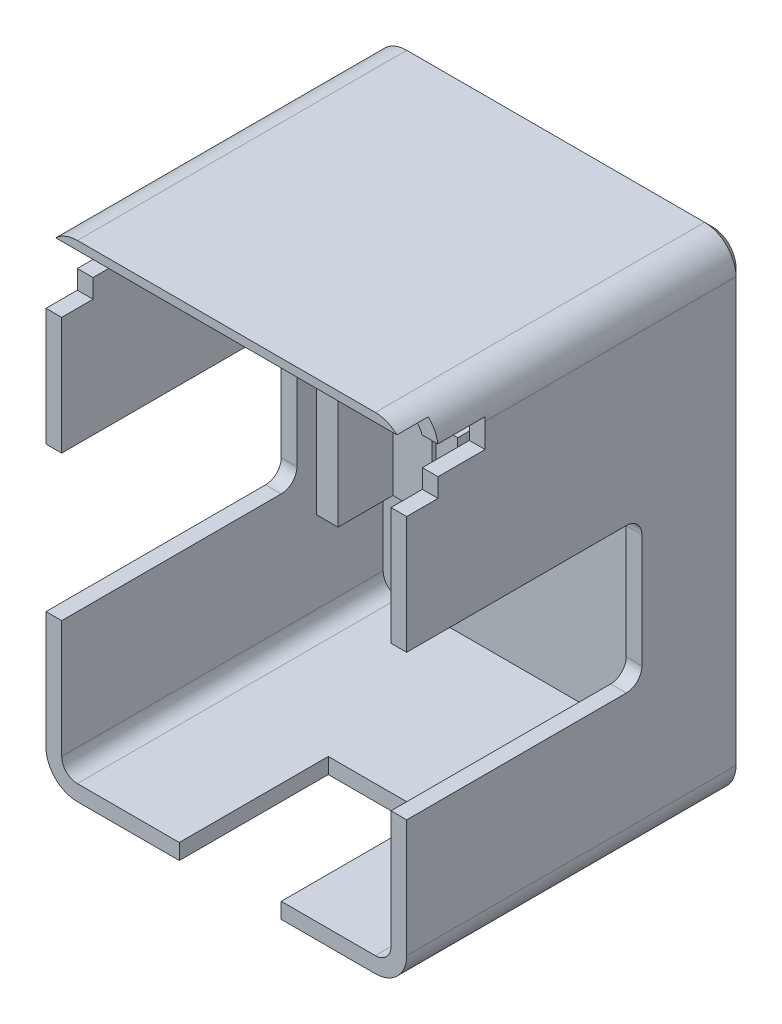
SolidWorks part; units mm, degrees
ref_plane "Plan de face" through (0, 0, 0) normal (0, 0, 1) x (1, 0, 0)
ref_plane "Plan de dessus" through (0, 0, 0) normal (0, 1, 0) x (1, 0, 0)
ref_plane "Plan de droite" through (0, 0, 0) normal (1, 0, 0) x (0, 0, -1)
sketch "Esquisse1" plane through (0, 0, 0) normal (0, 0, 1) x (1, 0, 0)
  line L1 (4, 0) -> (42, 0)
  line L2 (0, 4) -> (0, 58)
  line L3 (4, 62) -> (42, 62)
  line L4 (46, 4) -> (46, 58)
  arc A0 (42, 0) -> (46, 4) centre (42, 4) ccw
  arc A1 (0, 4) -> (4, 0) centre (4, 4) ccw
  arc A2 (0, 58) -> (4, 62) centre (4, 58) cw
  arc A3 (46, 58) -> (42, 62) centre (42, 58) ccw
  point P7 (46, 0)
  point P10 (0, 0)
  point P15 (46, 62)
  dimension "D3" = 4
  dimension "D1" = 46
  dimension "D2" = 62
extrude "Boss.-Extru.1" add sketch "Esquisse1" along normal blind 43
sketch "Esquisse3" plane through (0, 0, 43) normal (0, 0, 1) x (1, 0, 0)
  line L8 (2, 58) -> (2, 4)
  line L9 (4, 2) -> (42, 2)
  line L10 (44, 4) -> (44, 58)
  line L11 (42, 60) -> (4, 60)
  line L12 (2, 58) -> (2, 4)
  line L13 (4, 2) -> (42, 2)
  line L14 (44, 4) -> (44, 58)
  line L15 (42, 60) -> (4, 60)
  arc A4 (42, 2) -> (44, 4) centre (42, 4) ccw
  arc A5 (42, 2) -> (44, 4) centre (42, 4) ccw
  arc A6 (44, 58) -> (42, 60) centre (42, 58) ccw
  arc A7 (44, 58) -> (42, 60) centre (42, 58) ccw
  arc A8 (4, 60) -> (2, 58) centre (4, 58) ccw
  arc A9 (4, 60) -> (2, 58) centre (4, 58) ccw
  arc A10 (2, 4) -> (4, 2) centre (4, 4) ccw
  arc A11 (2, 4) -> (4, 2) centre (4, 4) ccw
  dimension "D1" = 2
extrude "Enlèv. mat.-Extru.1" cut sketch "Esquisse3" against normal blind 41
sketch "Esquisse4" plane through (46, 0, 0) normal (1, 0, 0) x (0, 0, -1)
  line L0 (-43, 62) -> (0, 62) construction
  line L1 (-58.5085, 60.9) -> (-39, 60.9)
  line L2 (-58.5085, 60.9) -> (-58.5085, 52.5)
  line L3 (-58.5085, 52.5) -> (-39, 52.5)
  line L4 (-39, 60.9) -> (-39, 58.5)
  line L5 (-39, 58.5) -> (-33, 58.5)
  line L7 (-39, 54.9) -> (-33, 54.9)
  line L8 (-33, 58.5) -> (-33, 54.9)
  line L9 (-43, 4) -> (-43, 58) construction
  line L10 (-39, 54.9) -> (-39, 52.5)
  dimension "D1" = 8.4
  dimension "D2" = 9.5
  dimension "D3" = 4
  dimension "D4" = 3.6
  dimension "D5" = 2.4
  dimension "D6" = 6
extrude "Enlèv. mat.-Extru.2" cut sketch "Esquisse4" against normal through all
chamfer "Chanfrein1" distance 1 angle 45 8 edges at (46, 31, 0) (44.8284, 60.8284, 0) (23, 62, 0) (1.1716, 60.8284, 0) (0, 31, 0) (1.1716, 1.1716, 0) (23, 0, 0) (44.8284, 1.1716, 0)
sketch "Esquisse5" plane through (46, 0, 0) normal (1, 0, 0) x (0, 0, -1)
  line L0 (-43, 0) -> (-1, 0) construction
  line L1 (-61.8969, 37.5) -> (-15, 37.5)
  line L2 (-61.8969, 37.5) -> (-61.8969, 19)
  line L3 (-61.8969, 19) -> (-15, 19)
  line L4 (-13, 35.5) -> (-13, 21)
  line L5 (-43, 4) -> (-43, 52.5) construction
  arc A0 (-15, 19) -> (-13, 21) centre (-15, 21) ccw
  arc A1 (-15, 37.5) -> (-13, 35.5) centre (-15, 35.5) cw
  dimension "D4" = 2
  dimension "D1" = 18.5
  dimension "D2" = 19
  dimension "D3" = 30
extrude "Enlèv. mat.-Extru.3" cut sketch "Esquisse5" against normal through all
sketch "Esquisse6" plane through (0, 0, 2) normal (0, 0, 1) x (1, 0, 0)
  line L0 (2, 52.5) -> (2, 37.5) construction
  line L1 (12, 47.45) -> (30, 47.45)
  line L2 (12, 47.45) -> (12, 24.45)
  line L3 (12, 24.45) -> (30, 24.45)
  line L4 (30, 47.45) -> (30, 24.45)
  line L7 (46, 54.9) -> (46, 58) construction
  point P6 (46, 56.45)
  dimension "D1" = 18
  dimension "D2" = 23
  dimension "D3" = 10
  dimension "D4" = 9
extrude "Boss.-Extru.2" add sketch "Esquisse6" along normal blind 18.5
sketch "Esquisse7" plane through (0, 0, 20.5) normal (0, 0, 1) x (1, 0, 0)
  line L0 (21, 50.8833) -> (21, 19.0211) construction
  line L1 (12, 41.95) -> (12, 47.45)
  line L2 (12, 47.45) -> (12, 24.45) construction
  line L3 (12, 41.95) -> (14.75, 41.95)
  line L4 (12, 47.45) -> (30, 47.45)
  line L5 (30, 24.45) -> (30, 47.45) construction
  line L8 (30, 47.45) -> (12, 47.45) construction
  line L9 (30, 47.45) -> (30, 41.95)
  line L10 (14.75, 24.45) -> (27.25, 24.45)
  line L12 (27.25, 41.95) -> (30, 41.95)
  line L14 (14.75, 41.95) -> (14.75, 24.45)
  line L15 (27.25, 41.95) -> (27.25, 24.45)
  line L16 (12, 24.45) -> (30, 24.45) construction
  point P15 (21, 47.45)
  dimension "D1" = 6.25
  dimension "D3" = 12.5
  dimension "D5" = 17.5
extrude "Enlèv. mat.-Extru.4" cut sketch "Esquisse7" against normal blind 7
sketch "Esquisse8" plane through (0, 0, 13.5) normal (0, 0, 1) x (1, 0, 0)
  line L0 (12, 47.45) -> (12, 41.95) construction
  line L1 (30, 41.95) -> (12, 41.95)
  line L2 (30, 41.95) -> (30, 43.95)
  line L3 (30, 43.95) -> (12, 43.95)
  line L4 (12, 41.95) -> (12, 43.95)
  dimension "D1" = 2
extrude "Enlèv. mat.-Extru.5" cut sketch "Esquisse8" against normal blind 5.5
sketch "Esquisse9" plane through (0, 0, 0) normal (0, -1, 0) x (1, 0, 0)
  line L1 (4, 43) -> (42, 43) construction
  line L2 (17, 43) -> (17, 24)
  line L3 (17, 24) -> (30, 24)
  line L4 (30, 43) -> (30, 24)
  line L5 (0, 43) -> (0, 1) construction
  line L6 (17, 43) -> (30, 43)
  line L7 (46, 43) -> (46, 1) construction
  dimension "D1" = 19
  dimension "D2" = 16
  dimension "D3" = 17
  dimension "D4" = 19
extrude "Enlèv. mat.-Extru.6" cut sketch "Esquisse9" against normal blind 3
chamfer "Chanfrein2" distance 0.5 angle 45 1 edges at (21, 43.95, 13.5)
sketch "Esquisse14" plane through (0, 0, 13.5) normal (0, 0, 1) x (1, 0, 0)
  line L0 (14.75, 24.45) -> (27.25, 24.45) construction
  line L1 (19.75, 24.45) -> (22.25, 24.45)
  line L2 (19.75, 24.45) -> (19.75, 41.95)
  line L3 (19.75, 41.95) -> (22.25, 41.95)
  line L4 (22.25, 24.45) -> (22.25, 41.95)
  line L5 (27.25, 41.95) -> (14.75, 41.95) construction
  line L6 (14.75, 41.95) -> (14.75, 24.45) construction
  line L7 (27.25, 24.45) -> (27.25, 41.95) construction
  dimension "D1" = 5
  dimension "D2" = 5
extrude "Enlèv. mat.-Extru.7" cut sketch "Esquisse14" against normal up to surface (11.5 mm away)
sketch "Esquisse15" plane through (0, 0, 2) normal (0, 0, 1) x (1, 0, 0)
  line L0 (2, 52.5) -> (2, 37.5) construction
  line L1 (2, 54.5) -> (7.5, 54.5)
  line L2 (2, 54.5) -> (2, 60)
  line L3 (2, 60) -> (7.5, 60)
  line L4 (7.5, 54.5) -> (7.5, 60)
  line L5 (42, 60) -> (4, 60) construction
  line L6 (44, 37.5) -> (44, 52.5) construction
  line L7 (38, 60) -> (44, 60)
  line L8 (38, 60) -> (38, 51.5)
  line L9 (38, 51.5) -> (44, 51.5)
  line L10 (44, 60) -> (44, 51.5)
  dimension "D1" = 5.5
  dimension "D2" = 5.5
  dimension "D3" = 8.5
  dimension "D4" = 6
extrude "Boss.-Extru.4" add sketch "Esquisse15" along normal blind 15
chamfer "Chanfrein3" distance 7 angle 30 1 edges at (7.5, 57.25, 17)
chamfer "Chanfrein4" distance 5 angle 30 1 edges at (38, 55.75, 17)
sketch "Esquisse16" plane through (44, 0, 0) normal (-1, 0, 0) x (0, 0, 1)
  line L0 (16.0622, 60) -> (39, 60) construction
  line L1 (17, 51.5) -> (27, 51.5)
  line L2 (17, 51.5) -> (17, 60)
  line L3 (17, 60) -> (27, 60)
  line L4 (27, 51.5) -> (27, 60)
  dimension "D1" = 10
extrude "Boss.-Extru.5" add sketch "Esquisse16" along normal up to vertex (3.1132 mm away) up to point (40.8867, 51.5, 17)
